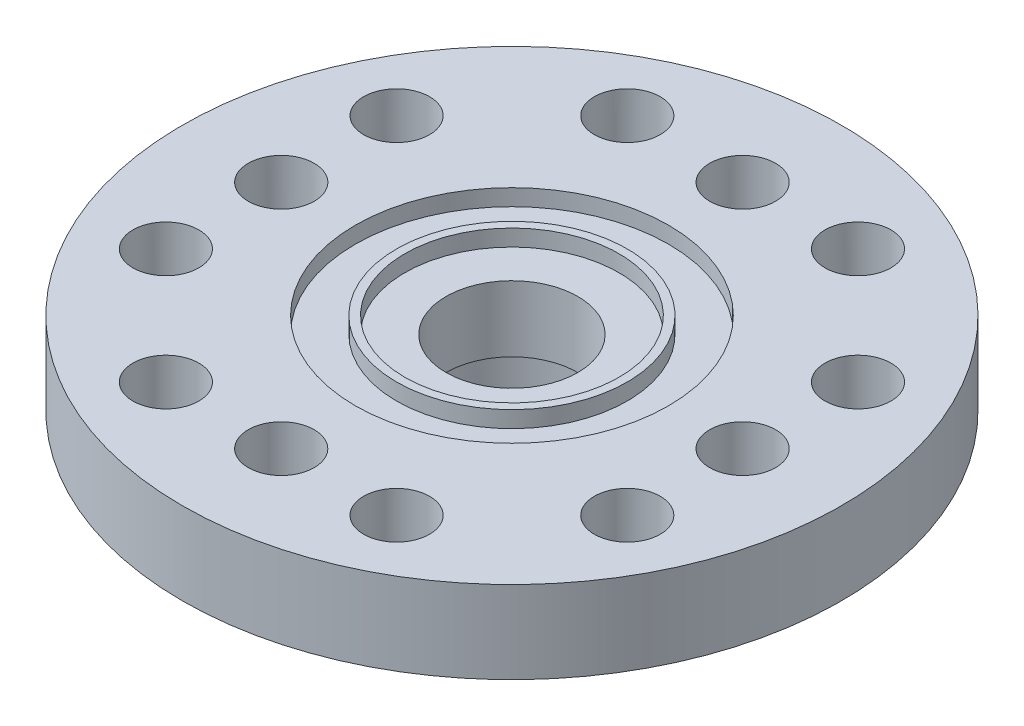
SolidWorks part; units mm, degrees
material "ABS"
ref_plane "Alzado" through (0, 0, 0) normal (0, 0, 1) x (1, 0, 0)
ref_plane "Planta" through (0, 0, 0) normal (0, 1, 0) x (1, 0, 0)
ref_plane "Vista lateral" through (0, 0, 0) normal (1, 0, 0) x (0, 0, -1)
sketch "Croquis1" plane through (0, 0, 0) normal (0, 1, 0) x (1, 0, 0)
  circle A0 centre (0, 0) radius 10
  dimension "D1" = 20
extrude "Saliente-Extruir1" add sketch "Croquis1" along normal blind 2.5
sketch "Croquis3" plane through (0, 0, 0) normal (0, -1, 0) x (1, 0, 0)
  circle A0 centre (0, 0) radius 4.5
  dimension "D1" = 9
extrude "Saliente-Extruir2" add sketch "Croquis3" along normal blind 3
sketch "Croquis4" plane through (0, 2.5, 0) normal (0, 1, 0) x (1, 0, 0)
  circle A0 centre (0, 0) radius 2
  dimension "D1" = 4
extrude "Cortar-Extruir1" cut sketch "Croquis4" against normal through all
sketch "Croquis5" plane through (0, -3, 0) normal (0, -1, 0) x (1, 0, 0)
  circle A0 centre (0, 0) radius 2.5
  dimension "D1" = 5
extrude "Cortar-Extruir2" cut sketch "Croquis5" against normal offset from surface (3 mm away) 2.5 up to face at (0, 2.5, 2)
sketch "Croquis6" plane through (0, 2.5, 0) normal (0, 1, 0) x (1, 0, 0)
  circle A0 centre (0, 0) radius 3.25
  circle A1 centre (0, 0) radius 3.5
  circle A2 centre (0, 0) radius 4.75
  circle M3 centre (0, 0) radius 2
  dimension "D1" = 0.25
  dimension "D2" = 7
  dimension "D3" = 9.5
extrude "Cortar-Extruir3" cut sketch "Croquis6" against normal blind 0.5 contours A0 M3 | A2 A1
sketch "Croquis7" plane through (0, 2.5, 0) normal (0, 1, 0) x (1, 0, 0)
  line L0 (3.5, -7) -> (-3.5, -7) construction
  line L1 (7, -3.5) -> (7, 3.5) construction
  line L2 (0, -10) -> (0, 10) construction
  line L3 (10, 0) -> (-10, 0) construction
  circle A0 centre (0, -7) radius 1
  circle A1 centre (3.5, -7) radius 1
  circle A2 centre (-3.5, -7) radius 1
  circle A3 centre (7, 3.5) radius 1
  circle A4 centre (7, 0) radius 1
  circle A5 centre (7, -3.5) radius 1
  circle A6 centre (0, 0) radius 10 construction
  circle A7 centre (-3.5, 7) radius 1
  circle A8 centre (0, 7) radius 1
  circle A9 centre (3.5, 7) radius 1
  circle A10 centre (-7, 3.5) radius 1
  circle A11 centre (-7, 0) radius 1
  circle A12 centre (-7, -3.5) radius 1
  point P5 (0, -7)
  point P10 (7, 0)
  dimension "D3" = 2
  dimension "D4" = 2
  dimension "D5" = 2
  dimension "D8" = 2
  dimension "D9" = 2
  dimension "D10" = 2
  dimension "D1" = 7
  dimension "D2" = 7
  dimension "D6" = 7
  dimension "D7" = 7
extrude "Cortar-Extruir4" cut sketch "Croquis7" against normal through all
